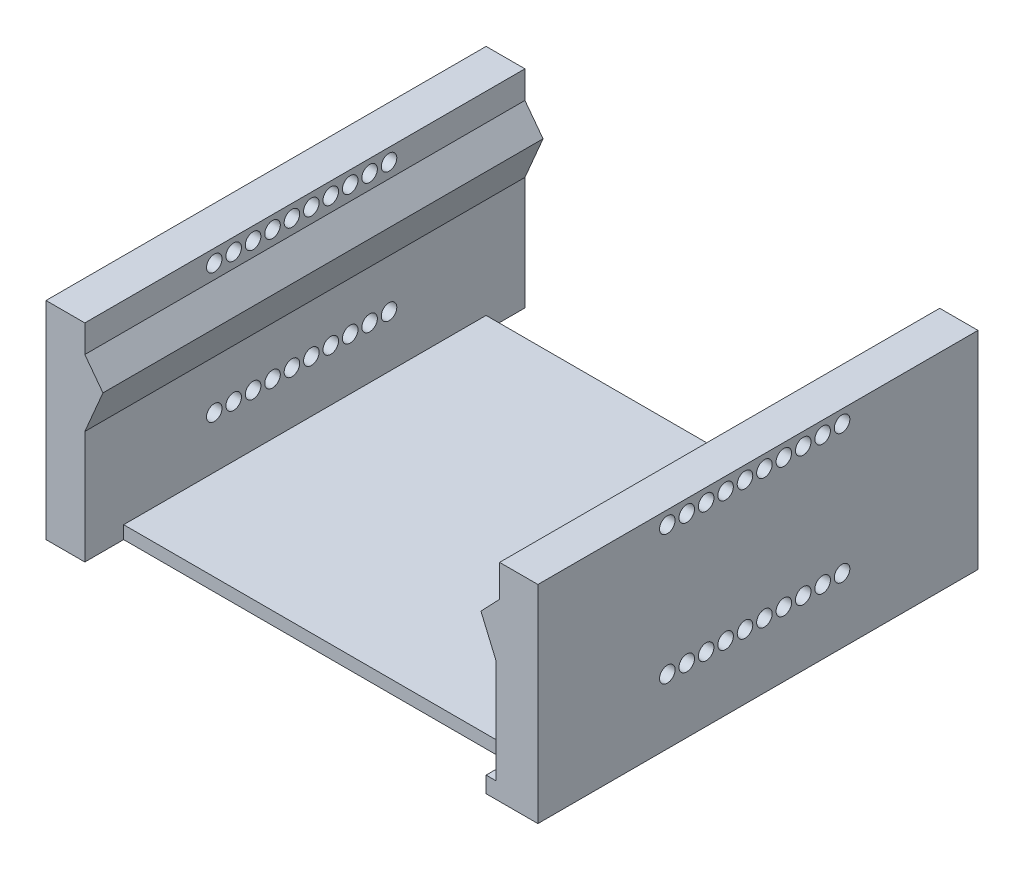
SolidWorks part; units mm, degrees
ref_plane "Front Plane" through (0, 0, 0) normal (0, 0, 1) x (1, 0, 0)
ref_plane "Top Plane" through (0, 0, 0) normal (0, 1, 0) x (1, 0, 0)
ref_plane "Right Plane" through (0, 0, 0) normal (1, 0, 0) x (0, 0, -1)
sketch "Sketch1" plane through (0, 0, 0) normal (0, 1, 0) x (1, 0, 0)
  line L1 (-16, -14) -> (16, -14)
  line L2 (-16, -14) -> (-16, 14)
  line L3 (-16, 14) -> (16, 14)
  line L4 (16, -14) -> (16, 14)
  line L5 (-16, -14) -> (16, 14) construction
  line L6 (-16, 14) -> (16, -14) construction
  point P0 (0, 0)
  dimension "D1" = 28
  dimension "D2" = 32
extrude "Boss-Extrude1" add sketch "Sketch1" along normal blind 1
sketch "Sketch2" plane through (0, 0, 0) normal (0, 1, 0) x (1, 0, 0)
  line L8 (19, -17) -> (19, 17)
  line L9 (-19, -17) -> (19, -17)
  line L10 (-19, 17) -> (-19, -17)
  line L11 (19, 17) -> (-19, 17)
  line L12 (19, -17) -> (19, 17)
  line L13 (-19, -17) -> (19, -17)
  line L14 (-19, 17) -> (-19, -17)
  line L15 (19, 17) -> (-19, 17)
  line L16 (16, -14) -> (16, 14)
  line L17 (-16, -14) -> (16, -14)
  line L18 (-16, 14) -> (-16, -14)
  line L19 (16, 14) -> (-16, 14)
  line L20 (16, -14) -> (16, 14)
  line L21 (-16, -14) -> (16, -14)
  line L22 (-16, 14) -> (-16, -14)
  line L23 (16, 14) -> (-16, 14)
  dimension "D1" = 3
  dimension "D2" = 0
extrude "Boss-Extrude2" add sketch "Sketch2" along normal blind 16
sketch "Sketch3" plane through (0, 16, 0) normal (0, 1, 0) x (1, 0, 0)
  line L0 (19, 17) -> (-19, 17) construction
  line L1 (-16, 14) -> (15, 14)
  line L2 (-16, 14) -> (-16, 17)
  line L3 (-16, 17) -> (15, 17)
  line L4 (15, 14) -> (15, 17)
  line L5 (-19, -17) -> (19, -17) construction
  line L6 (-16, -14) -> (15, -14)
  line L7 (-16, -14) -> (-16, -17)
  line L8 (-16, -17) -> (15, -17)
  line L9 (15, -14) -> (15, -17)
extrude "Cut-Extrude1" cut sketch "Sketch3" against normal blind 16
sketch "Sketch4" plane through (19, 0, 0) normal (1, 0, 0) x (0, 0, -1)
  line L0 (-17, 16) -> (17, 16) construction
  line L1 (-17, 16) -> (-17, 0) construction
  circle A0 centre (-7, 15) radius 0.6
  circle A1 centre (-5.5, 15) radius 0.6
  circle A2 centre (-4, 15) radius 0.6
  circle A3 centre (-2.5, 15) radius 0.6
  circle A4 centre (-1, 15) radius 0.6
  circle A5 centre (0.5, 15) radius 0.6
  circle A6 centre (2, 15) radius 0.6
  circle A7 centre (3.5, 15) radius 0.6
  circle A8 centre (5, 15) radius 0.6
  circle A9 centre (6.5, 15) radius 0.6
  circle A10 centre (-5.5, 15) radius 0.6
  circle A11 centre (-4, 15) radius 0.6
  circle A12 centre (-2.5, 15) radius 0.6
  circle A13 centre (-1, 15) radius 0.6
  circle A14 centre (0.5, 15) radius 0.6
  circle A15 centre (2, 15) radius 0.6
  circle A16 centre (3.5, 15) radius 0.6
  circle A17 centre (5, 15) radius 0.6
  circle A18 centre (6.5, 15) radius 0.6
  circle A19 centre (-5.5, 10) radius 0.6
  circle A20 centre (-4, 10) radius 0.6
  circle A21 centre (-2.5, 10) radius 0.6
  circle A22 centre (-1, 10) radius 0.6
  circle A23 centre (0.5, 10) radius 0.6
  circle A24 centre (2, 10) radius 0.6
  circle A25 centre (3.5, 10) radius 0.6
  circle A26 centre (5, 10) radius 0.6
  circle A27 centre (6.5, 10) radius 0.6
  circle A28 centre (-7, 10) radius 0.6
  dimension "D1" = 1.2
  dimension "D8" = 4.5
  dimension "D2" = 1
  dimension "D3" = 10
  dimension "D7" = 10
  dimension "D4" = 10
  dimension "D5" = 10
  dimension "D6" = 2
extrude "Cut-Extrude2" cut sketch "Sketch4" against normal blind 61 contours A0 | A1 | A2 | A3 | A4 | A5 | A6 | A7 | A8 | A9 | A27 | A26 | A25 | A24 | A23 | A22 | A21 | A20 | A19 | A28
sketch "Sketch6" plane through (0, 0, 17) normal (0, 0, 1) x (1, 0, 0)
  line L0 (-16, 13.8823) -> (-14.6, 12.0187)
  line L1 (-16, 0) -> (-16, 16) construction
  line L2 (-14.6, 12.0187) -> (-16, 8.7361)
  line L3 (-16, 13.8823) -> (-16, 8.7361)
  line L4 (0, 0) -> (0, 18.9056) construction
  line L5 (14.6, 12.0187) -> (16, 8.7361)
  line L6 (16, 13.8823) -> (16, 8.7361)
  line L7 (16, 13.8823) -> (14.6, 12.0187)
  dimension "D1" = 1.4
extrude "Boss-Extrude3" add sketch "Sketch6" against normal up to surface (34 mm away) up to face at (-17.5, 8, -17)
sketch "Sketch9" plane through (-19, 0, 0) normal (-1, 0, 0) x (0, 0, 1)
  circle A0 centre (-6.5, 5) radius 0.6
  circle A1 centre (-6.5, 15) radius 0.6 construction
  circle A2 centre (-5, 5) radius 0.6
  circle A3 centre (-3.5, 5) radius 0.6
  circle A4 centre (-2, 5) radius 0.6
  circle A5 centre (-0.5, 5) radius 0.6
  circle A6 centre (1, 5) radius 0.6
  circle A7 centre (2.5, 5) radius 0.6
  circle A8 centre (4, 5) radius 0.6
  circle A9 centre (5.5, 5) radius 0.6
  circle A10 centre (7, 5) radius 0.6
  dimension "D1" = 1.2
  dimension "D3" = 0
  dimension "D2" = 10
  dimension "D4" = 10
extrude "Cut-Extrude3" cut sketch "Sketch9" against normal blind 45
sketch "Sketch10" plane through (-19, 0, 0) normal (-1, 0, 0) x (0, 0, 1)
  line L1 (-8.4645, 12.1392) -> (12.2172, 12.1392)
  line L2 (-8.4645, 12.1392) -> (-8.4645, 7.2736)
  line L3 (-8.4645, 7.2736) -> (12.2172, 7.2736)
  line L4 (12.2172, 12.1392) -> (12.2172, 7.2736)
extrude "Boss-Extrude4" add sketch "Sketch10" against normal blind 3
sketch "Sketch11" plane through (19, 0, 0) normal (1, 0, 0) x (0, 0, -1)
  line L1 (-9.486, 12.704) -> (10.7315, 12.704)
  line L2 (-9.486, 12.704) -> (-9.486, 8.0144)
  line L3 (-9.486, 8.0144) -> (10.7315, 8.0144)
  line L4 (10.7315, 12.704) -> (10.7315, 8.0144)
extrude "Boss-Extrude5" add sketch "Sketch11" against normal blind 3
sketch "Sketch12" plane through (0, 0, 17) normal (0, 0, 1) x (1, 0, 0)
  line L0 (14.6, 12.0187) -> (16.0414, 13.5289)
  line L1 (16.0414, 13.5289) -> (16.0414, 16)
  line L2 (15, 16) -> (19, 16) construction
  line L3 (16.0414, 16) -> (15, 16)
  line L4 (15, 16) -> (13.5558, 12.0187)
  line L5 (14.6, 12.0187) -> (14.8821, 11.3572)
  line L6 (14.6, 12.0187) -> (15, 11.0808) construction
  line L7 (14.8821, 11.3572) -> (15.7477, 9.3277)
  line L8 (15.7477, 9.3277) -> (15.7477, 1.248)
  line L9 (15.7477, 1.248) -> (9.4419, 1.248)
  line L10 (9.4419, 1.248) -> (11.7448, 12.1499)
  line L11 (11.7448, 12.1499) -> (13.5558, 12.0187)
extrude "Cut-Extrude5" cut sketch "Sketch12" against normal through all
